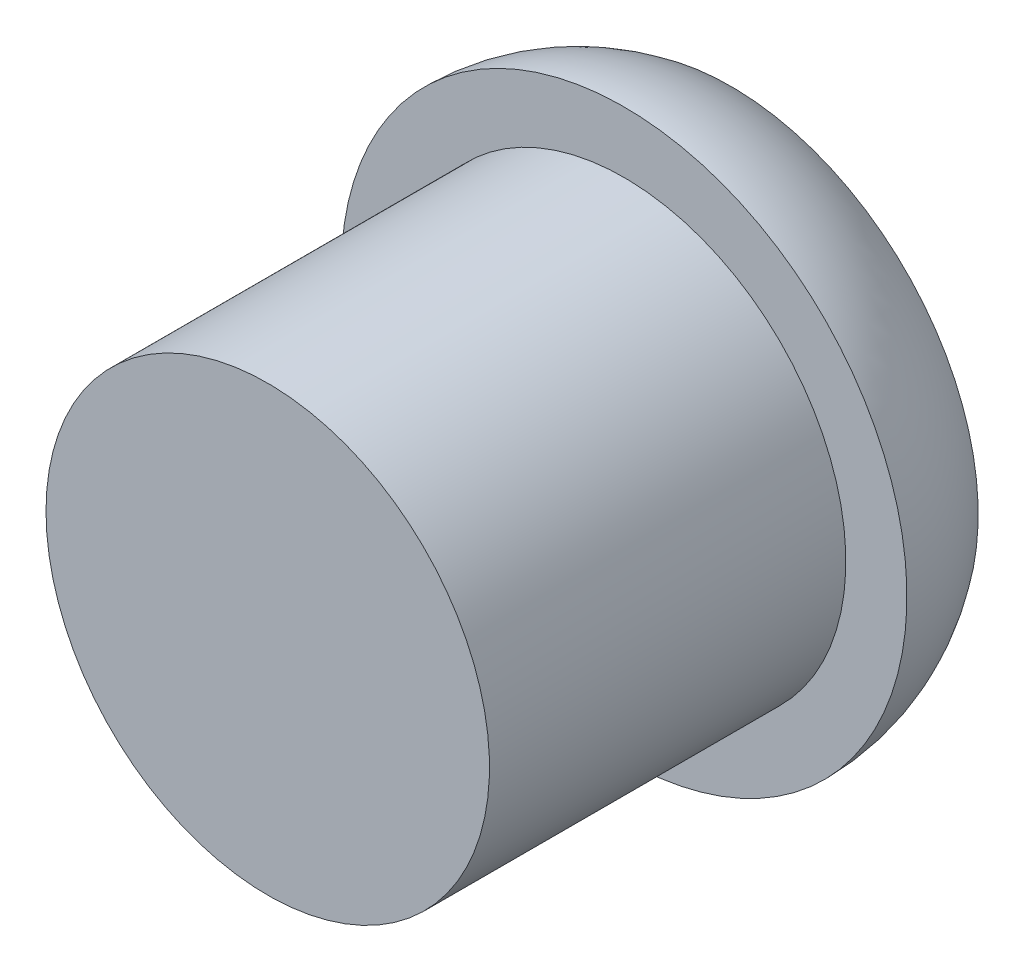
SolidWorks part; units mm, degrees
material "ABS"
ref_plane "Ground_Plane" through (0, 0, 0) normal (0, 0, 1) x (1, 0, 0)
ref_plane "VehicleCentre_Plane" through (0, 0, 0) normal (0, 1, 0) x (1, 0, 0)
ref_plane "FrontAxle_Plane" through (0, 0, 0) normal (1, 0, 0) x (0, 0, -1)
sketch "Sketch1" plane through (0, 0, 0) normal (0, 1, 0) x (1, 0, 0)
  line L0 (0, -10) -> (6.223, -10)
  line L1 (6.223, -10) -> (6.223, 0)
  line L2 (6.223, 0) -> (7.9375, 0)
  line L3 (6.9375, 3) -> (6.245, 3)
  line L4 (0, 6) -> (0, -10)
  arc A0 (7.9375, 0) -> (6.9375, 3) centre (2.9375, 0) ccw
  arc A1 (6.245, 3) -> (0, 6) centre (0, -2) ccw
  dimension "D4" = 5
  dimension "D5" = 8
  dimension "D1" = 6.223
  dimension "D2" = 7.9375
  dimension "D3" = 3
  dimension "D6" = 2
  dimension "D7" = 10
revolve "Revolve1" add sketch "Sketch1" angle 360 about L4
